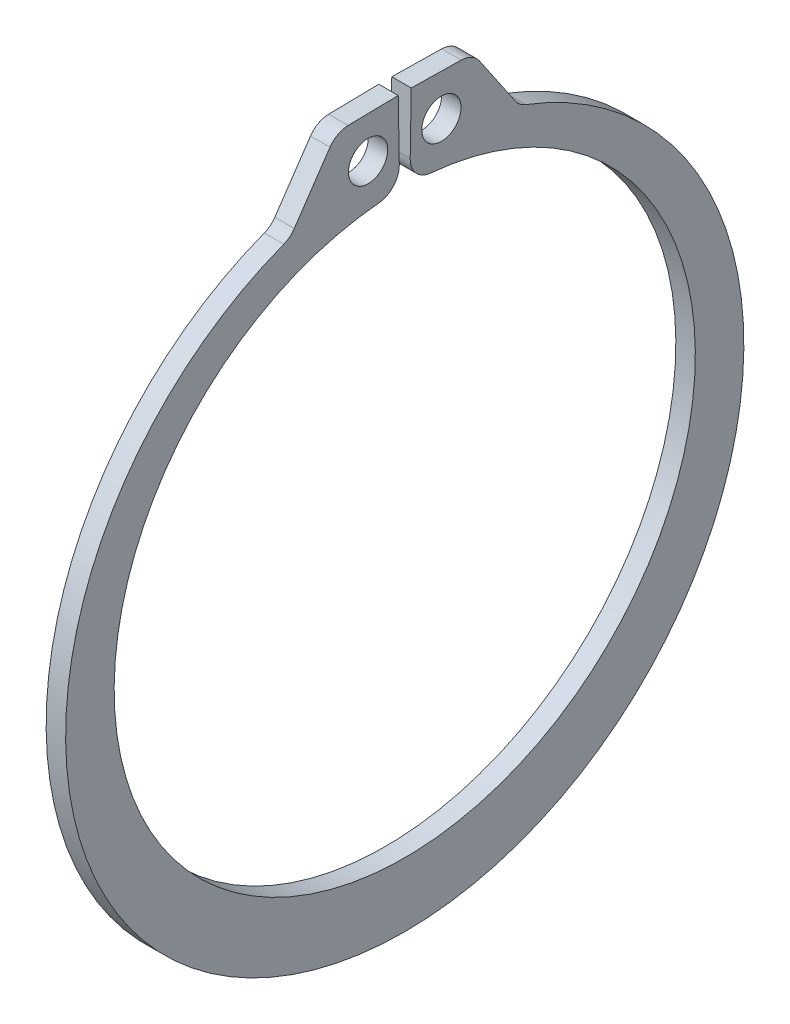
SolidWorks part; units mm, degrees
material "Cast Carbon Steel"
ref_plane "Front" through (0, 0, 0) normal (0, 0, 1) x (1, 0, 0)
ref_plane "Top" through (0, 0, 0) normal (0, 1, 0) x (1, 0, 0)
ref_plane "Right" through (0, 0, 0) normal (1, 0, 0) x (0, 0, -1)
sketch "Sketch1" plane through (0, 0, 0) normal (1, 0, 0) x (0, 0, -1)
  line L0 (0, 0) -> (0, 23.495) construction
  line L1 (-0.41, 23.4914) -> (-0.5262, 30.1452)
  line L2 (0.5262, 30.1452) -> (5.5165, 30.0581)
  line L3 (5.5165, 30.0581) -> (9.2542, 24.5521)
  line L4 (0.41, 23.4914) -> (0.5262, 30.1452)
  line L5 (-0.5262, 30.1452) -> (-5.5165, 30.0581)
  line L6 (-5.5165, 30.0581) -> (-9.2542, 24.5521)
  line L7 (-9.2542, 24.5521) -> (-8.2866, 21.9851) construction
  line L8 (9.2542, 24.5521) -> (8.2866, 21.9851) construction
  line L9 (0, -23.495) -> (0, -28.6766) construction
  line L10 (-5.5165, 30.0581) -> (-0.41, 23.4914) construction
  line L11 (0, 23.495) -> (0, 30.1498) construction
  line L12 (-23.495, 0) -> (23.495, 0) construction
  circle A0 centre (0, 0) radius 23.495 construction
  arc A1 (-0.41, 23.4914) -> (0.41, 23.4914) centre (0, 0) ccw
  circle A4 centre (-2.9633, 26.7748) radius 1.5875
  circle A5 centre (2.9633, 26.7748) radius 1.5875
  arc A6 (-9.2542, 24.5521) -> (9.2542, 24.5521) centre (0, -1.2578) ccw construction
  point P0 (0, -28.6766)
  dimension "Ring ID" = 46.99
  dimension "Hole Diameter" = 3.175
  dimension "Min. Sec." = 2.7432
  dimension "Max. Sec." = 5.1816
  dimension "Lug Height" = 6.6548
  dimension "D2" = 4.9911
  dimension "Angle" = 1
sketch "Sketch2" plane through (0, 0, 0) normal (0, 1, 0) x (1, 0, 0)
  line L0 (-0.7874, -27.3899) -> (0.7874, -27.3899) construction
  line L1 (0, -27.4188) -> (0, 27.4188) construction
  point P8 (0, -27.3899)
  dimension "Ring Thickness" = 1.5748
sketch "Sketch3" plane through (0, 0, 0) normal (1, 0, 0) x (0, 0, -1)
  line L0 (-5.5165, 30.0581) -> (-9.2542, 24.5521) construction
  line L1 (-5.5165, 30.0581) -> (-9.2542, 24.5521)
  line L2 (-0.5262, 30.1452) -> (-5.5165, 30.0581) construction
  line L3 (-0.5262, 30.1452) -> (-5.5165, 30.0581)
  line L4 (-0.41, 23.4914) -> (-0.5262, 30.1452) construction
  line L5 (-0.41, 23.4914) -> (-0.5262, 30.1452)
  line L6 (0.41, 23.4914) -> (0.5262, 30.1452) construction
  line L7 (0.41, 23.4914) -> (0.5262, 30.1452)
  line L8 (0.5262, 30.1452) -> (5.5165, 30.0581) construction
  line L9 (0.5262, 30.1452) -> (5.5165, 30.0581)
  line L10 (5.5165, 30.0581) -> (9.2542, 24.5521) construction
  line L11 (5.5165, 30.0581) -> (9.2542, 24.5521)
  arc A0 (-9.2542, 24.5521) -> (9.2542, 24.5521) centre (0, -1.2578) ccw construction
  arc A1 (-9.2542, 24.5521) -> (9.2542, 24.5521) centre (0, -1.2578) ccw
  arc A2 (-0.41, 23.4914) -> (0.41, 23.4914) centre (0, 0) ccw construction
  arc A3 (-0.41, 23.4914) -> (0.41, 23.4914) centre (0, 0) ccw
  circle A4 centre (-2.9633, 26.7748) radius 1.5875 construction
  circle A5 centre (-2.9633, 26.7748) radius 1.5875
  circle A6 centre (2.9633, 26.7748) radius 1.5875 construction
  circle A7 centre (2.9633, 26.7748) radius 1.5875
extrude "Boss-Extrude1" add sketch "Sketch3" along normal up to vertex (0.7874 mm away) and the other way up to vertex (0.7874 mm away) up to point (0.7874, 0, 27.3899) other way up to point (-0.7874, 0, 27.3899)
fillet "Fillet1" radius 1.8161 6 edges at (0, 24.5521, -9.2542) (0, 30.0581, -5.5165) (0, 23.4914, -0.41) (0, 23.4914, 0.41) (0, 30.0581, 5.5165) (0, 24.5521, 9.2542)
sketch "Sketch4" plane through (0, 0, 0) normal (1, 0, 0) x (0, 0, -1)
  line L0 (-20.3473, 11.7475) -> (0, 0) construction
  line L1 (0, 0) -> (0, 23.495) construction
  line L2 (0, 30.1498) -> (0, 23.495) construction
  arc A0 (-0.41, 23.4914) -> (0.41, 23.4914) centre (0, 0) ccw construction
  point P0 (0, 0)
  point P1 (-20.3473, 11.7475)
  dimension "D1" = 60
equation "\"D2@Sketch1\" = \"Lug Height@Sketch1\" * .75"
